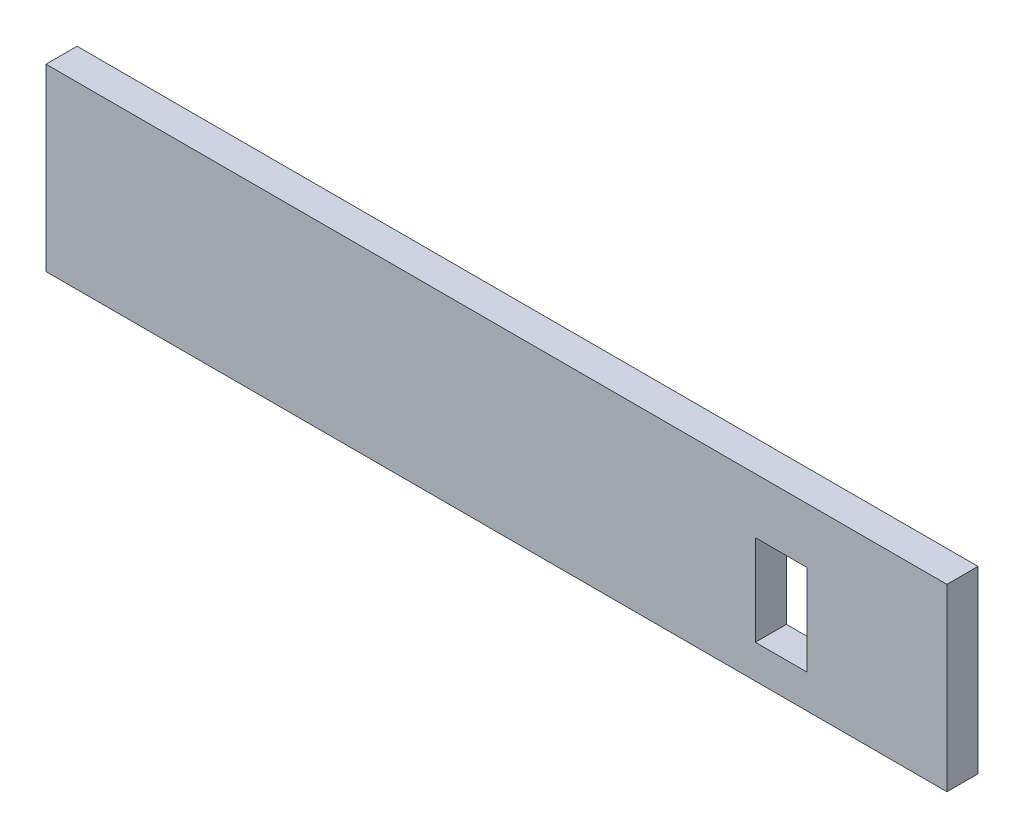
SolidWorks part; units mm, degrees
material "Pine"
ref_plane "Front Plane" through (0, 0, 0) normal (0, 0, 1) x (1, 0, 0)
ref_plane "Top Plane" through (0, 0, 0) normal (0, 1, 0) x (1, 0, 0)
ref_plane "Right Plane" through (0, 0, 0) normal (1, 0, 0) x (0, 0, -1)
sketch "Sketch1" plane through (0, 0, 0) normal (0, 0, 1) x (1, 0, 0)
  line L1 (-276.225, -55.0723) -> (276.225, -55.0723)
  line L2 (-276.225, -55.0723) -> (-276.225, 55.0723)
  line L3 (-276.225, 55.0723) -> (276.225, 55.0723)
  line L4 (276.225, -55.0723) -> (276.225, 55.0723)
  line L5 (-276.225, -55.0723) -> (276.225, 55.0723) construction
  line L6 (-276.225, 55.0723) -> (276.225, -55.0723) construction
  point P0 (0, 0)
  dimension "D1" = 552.45
  dimension "D2" = 110.1446
extrude "Boss-Extrude1" add sketch "Sketch1" along normal blind 19.05
sketch "Sketch2" plane through (0, 0, 0) normal (0, 0, -1) x (-1, 0, 0)
  line L0 (-276.225, -55.0723) -> (-276.225, 55.0723) construction
  line L1 (-190.5, 21.1277) -> (-158.75, 21.1277)
  line L2 (-190.5, 21.1277) -> (-190.5, -34.4348)
  line L3 (-190.5, -34.4348) -> (-158.75, -34.4348)
  line L4 (-158.75, 21.1277) -> (-158.75, -34.4348)
  line L5 (276.225, -55.0723) -> (-276.225, -55.0723) construction
  dimension "D1" = 85.725
  dimension "D2" = 20.6375
  dimension "D3" = 31.75
  dimension "D4" = 55.5625
extrude "Cut-Extrude1" cut sketch "Sketch2" against normal through all
equation "\"2.5325‬\"=6.68551"
